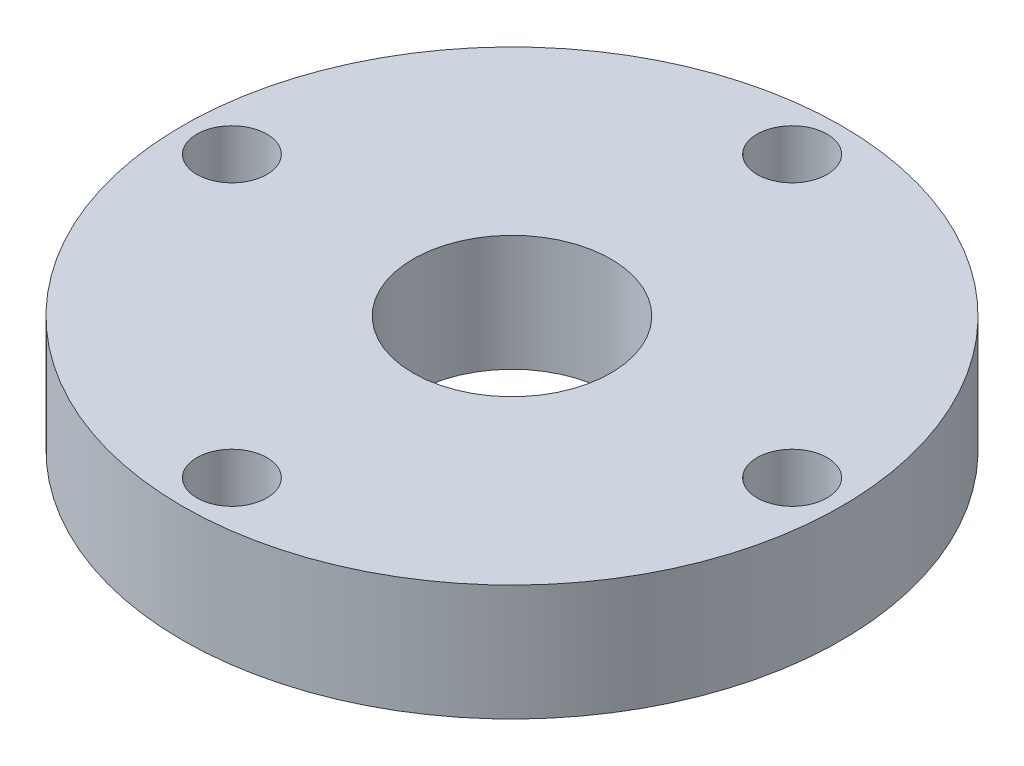
SolidWorks part; units mm, degrees
ref_plane "Front Plane" through (0, 0, 0) normal (1, 0, 0) x (0, 1, 0)
ref_plane "Top Plane" through (0, 0, 0) normal (0, 0, 1) x (0, 1, 0)
ref_plane "Right Plane" through (0, 0, 0) normal (0, 1, 0) x (-1, 0, 0)
sketch "Sketch1" plane through (0, 0, 0) normal (0, 0, 1) x (0, 1, 0)
  line L0 (-11.176, 0) -> (-11.176, 63.5)
  line L1 (-11.176, 63.5) -> (11.176, 63.5)
  line L2 (11.176, 63.5) -> (11.176, 0)
  line L3 (11.176, 0) -> (-11.176, 0)
  line L4 (-36.576, 0) -> (36.576, 0) construction
  point P6 (0, 0)
  dimension "D1" = 22.352
  dimension "D2" = 63.5
revolve "Revolve1" add sketch "Sketch1" angle 360 about L4
sketch "Sketch2" plane through (0, 0, 0) normal (0, 1, 0) x (-1, 0, 0)
  circle A0 centre (0, 0) radius 19.05
  point P3 (0, 0)
  dimension "D1" = 38.1
extrude "Cut-Extrude2" cut sketch "Sketch2" against normal through all from offset 11.176
hole_wizard "CBORE for 5/16 Socket Head Cap Screw1" positions "Sketch4" profile "Sketch3" counterbore size "5/16" standard "ANSI Inch"
sketch "Sketch4" plane through (0, 11.176, 0) normal (0, 1, 0) x (1, 0, 0)
  circle A0 centre (0, 0) radius 53.975 construction
  circle A1 centre (0, 0) radius 19.05 construction
  point P0 (-53.975, 0)
  point P1 (0, -53.975)
  point P3 (53.975, 0)
  point P5 (0, 53.975)
  dimension "D1" = 107.95
  dimension "D2" = 53.975
  dimension "D3" = 53.975
  dimension "D4" = 53.975
  dimension "D5" = 53.975
sketch "Sketch3" plane through (-53.975, 11.176, 0) normal (1, 0, 0) x (0, 0, 1)
  line L0 (0, 0) -> (0, 24.977)
  line L1 (0, 24.977) -> (4.3688, 22.352)
  line L2 (4.3688, 22.352) -> (4.3688, 9.652)
  line L3 (4.3688, 9.652) -> (6.7437, 9.652)
  line L4 (6.7437, 9.652) -> (6.7437, 0)
  line L5 (6.7437, 0) -> (0, 0)
  line L10 (0, 24.977) -> (-4.3688, 22.352) construction
  line L11 (0, -6.35) -> (0, 107.95) construction
  dimension "Hole Dia." = 8.7376
  dimension "Hole Depth" = 22.352
  dimension "C'Bore Dia." = 13.4874
  dimension "C'Bore Depth" = 9.652
  dimension "Drill Angle" = 118
